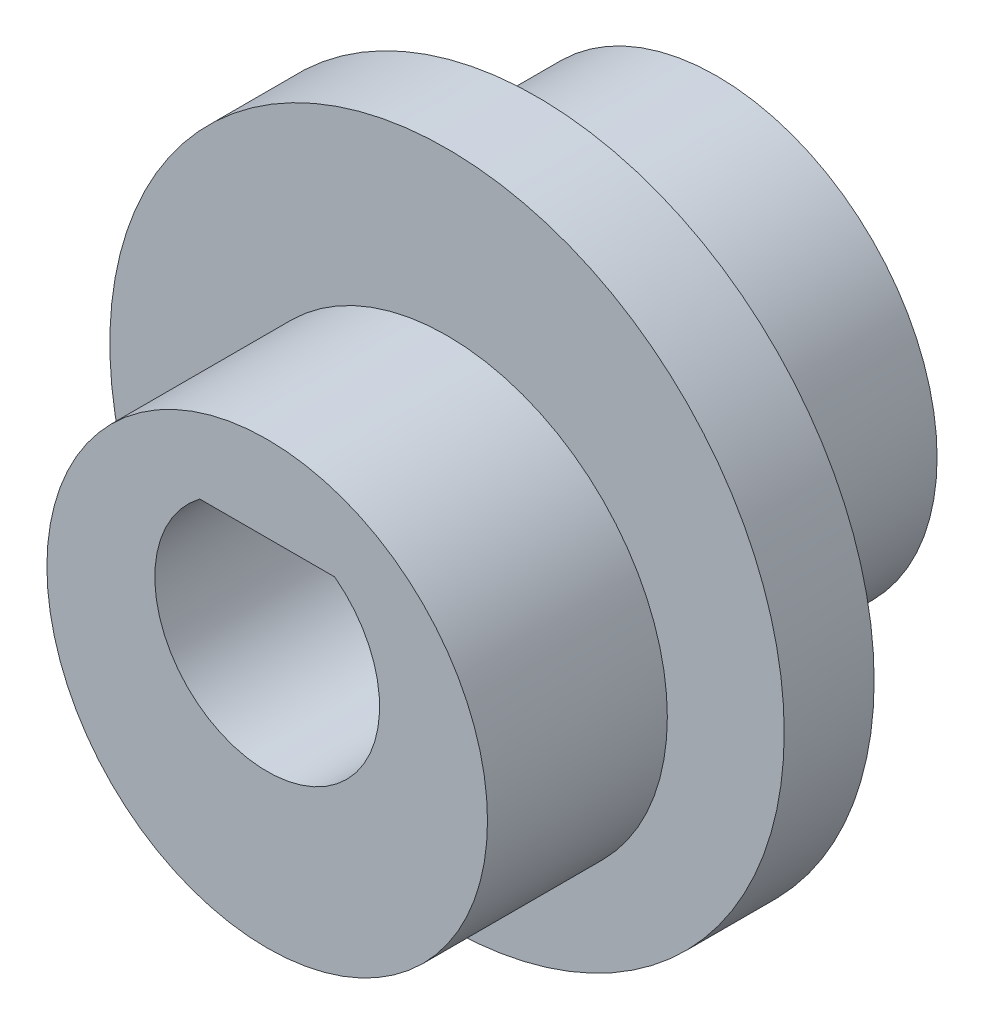
SolidWorks part; units mm, degrees
ref_plane "Plan de face" through (0, 0, 0) normal (0, 0, 1) x (1, 0, 0)
ref_plane "Plan de dessus" through (0, 0, 0) normal (0, 1, 0) x (1, 0, 0)
ref_plane "Plan de droite" through (0, 0, 0) normal (1, 0, 0) x (0, 0, -1)
sketch "Esquisse1" plane through (0, 0, 0) normal (0, 0, 1) x (1, 0, 0)
  circle A2 centre (0, 1) radius 4.9
  dimension "D1" = 1
  dimension "D4" = 9.8
extrude "Boss.-Extru.1" add sketch "Esquisse1" along normal blind 4
sketch "Esquisse4" plane through (0, 0, 4) normal (0, 0, 1) x (1, 0, 0)
  circle A0 centre (0, 0) radius 7.5
  dimension "D1" = 15
extrude "Boss.-Extru.4" add sketch "Esquisse4" along normal blind 2
sketch "Esquisse5" plane through (0, 0, 6) normal (0, 0, 1) x (1, 0, 0)
  circle A0 centre (0, -1) radius 4.9
  dimension "D1" = 9.8
  dimension "D2" = 1
extrude "Boss.-Extru.5" add sketch "Esquisse5" along normal blind 4
sketch "Esquisse6" plane through (0, 0, 10) normal (0, 0, 1) x (1, 0, 0)
  line L0 (-1.5, 2) -> (1.5, 2)
  arc A0 (-1.5, 2) -> (1.5, 2) centre (0, 0) ccw
  dimension "D1" = 5
  dimension "D2" = 2
extrude "Enlèv. mat.-Extru.1" cut sketch "Esquisse6" against normal through all
